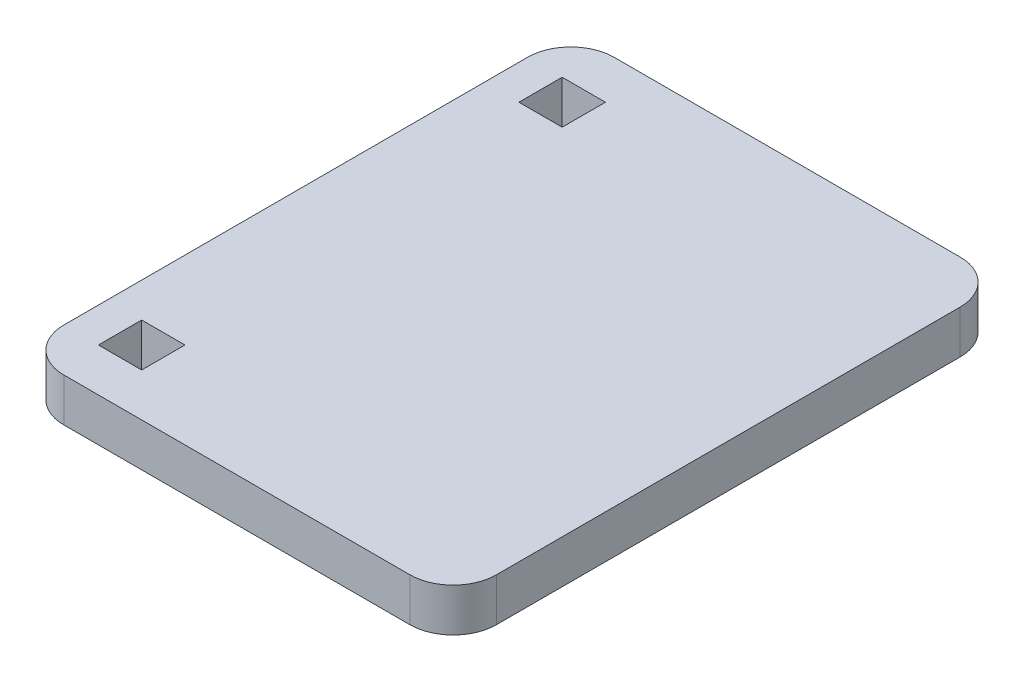
SolidWorks part; units mm, degrees
ref_plane "Front Plane" through (0, 0, 0) normal (0, 0, 1) x (1, 0, 0)
ref_plane "Top Plane" through (0, 0, 0) normal (0, 1, 0) x (1, 0, 0)
ref_plane "Right Plane" through (0, 0, 0) normal (1, 0, 0) x (0, 0, -1)
sketch "Sketch2" plane through (0, 0, 0) normal (0, 1, 0) x (1, 0, 0)
  line L0 (25, 0) -> (25, -63.6) construction
  line L1 (5, 0) -> (45, 0)
  line L2 (0, -5) -> (0, -58.6)
  line L3 (5, -63.6) -> (45, -63.6)
  line L4 (50, -5) -> (50, -58.6)
  line L5 (0, -31.8) -> (50, -31.8) construction
  line L6 (9, -53.6) -> (9, -58.6)
  line L7 (4, -10) -> (9, -10)
  line L8 (4, -10) -> (4, -5)
  line L9 (4, -5) -> (9, -5)
  line L10 (9, -10) -> (9, -5)
  line L11 (4, -10) -> (9, -5) construction
  line L12 (4, -5) -> (9, -10) construction
  line L13 (4, -53.6) -> (9, -53.6)
  line L14 (4, -53.6) -> (4, -58.6)
  line L15 (4, -58.6) -> (9, -58.6)
  line L16 (4, -53.6) -> (9, -58.6) construction
  arc A0 (0, -58.6) -> (5, -63.6) centre (5, -58.6) ccw
  arc A1 (45, -63.6) -> (50, -58.6) centre (45, -58.6) ccw
  arc A2 (50, -5) -> (45, 0) centre (45, -5) ccw
  arc A3 (0, -5) -> (5, 0) centre (5, -5) cw
  point P7 (0, -63.6)
  point P10 (50, -63.6)
  point P13 (50, 0)
  point P16 (0, 0)
  point P21 (6.5, -7.5)
  point P22 (43.5, -25)
  point P31 (6.5, -56.1)
  dimension "D3" = 5
  dimension "D4" = 7.5
  dimension "D5" = 5
  dimension "D1" = 50
  dimension "D2" = 48.6
  dimension "D7" = 5
extrude "Boss-Extrude1" add sketch "Sketch2" along normal blind 5
